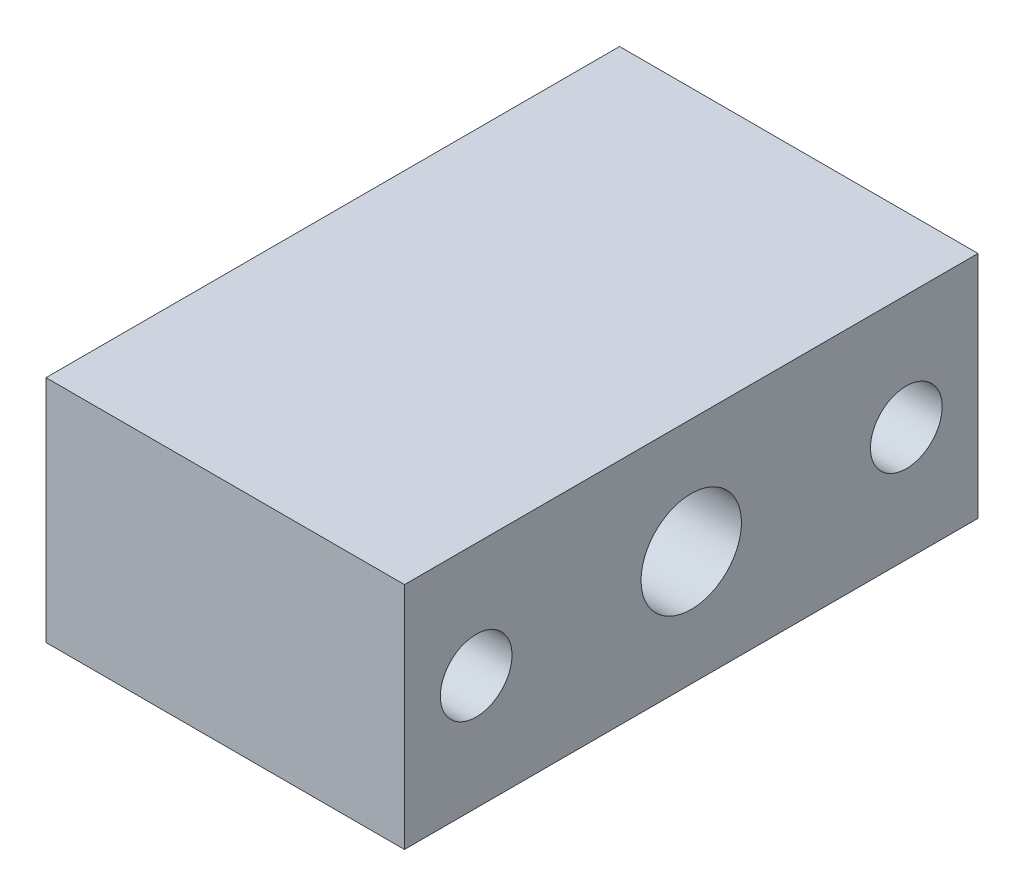
SolidWorks part; units mm, degrees
ref_plane "前视基准面" through (0, 0, 0) normal (0, 0, 1) x (1, 0, 0)
ref_plane "上视基准面" through (0, 0, 0) normal (0, 1, 0) x (1, 0, 0)
ref_plane "右视基准面" through (0, 0, 0) normal (1, 0, 0) x (0, 0, -1)
sketch "草图1" plane through (0, 0, 0) normal (1, 0, 0) x (0, 0, -1)
  line L1 (-40, -16) -> (40, -16)
  line L2 (-40, -16) -> (-40, 16)
  line L3 (-40, 16) -> (40, 16)
  line L4 (40, -16) -> (40, 16)
  line L5 (-40, -16) -> (40, 16) construction
  line L6 (-40, 16) -> (40, -16) construction
  point P0 (0, 0)
  dimension "D1" = 32
  dimension "D2" = 80
extrude "凸台-拉伸1" add sketch "草图1" along normal blind 50
hole_wizard "M16 螺纹孔1" positions "草图3" profile "草图4" tap size "M16" standard "GB" end condition through all
sketch "草图3" plane through (0, 0, 0) normal (-1, 0, 0) x (0, 0, 1)
  point P0 (0, 0)
sketch "草图4" plane through (0, 0, 0) normal (0, 1, 0) x (0, 0, 1)
  line L0 (0, 0) -> (0, 50)
  line L1 (0, 50) -> (7, 50)
  line L2 (7, 50) -> (7, 0)
  line L5 (7, 0) -> (0, 0)
  line L11 (0, -6.35) -> (0, 107.95) construction
  dimension "通孔螺纹孔钻头直径" = 14
  dimension "通孔螺纹孔钻头深度" = 50
cosmetic thread "孔螺纹线1"
sketch "草图5" plane through (0, 0, 0) normal (-1, 0, 0) x (0, 0, 1)
  line L0 (40, 16) -> (40, -16) construction
  circle A0 centre (30, 0) radius 5
  dimension "D1" = 10
  dimension "D2" = 10
extrude "切除-拉伸1" cut sketch "草图5" against normal through all
mirror "镜向1" about plane through (0, 0, 0) normal (0, 0, 1) of "切除-拉伸1"
